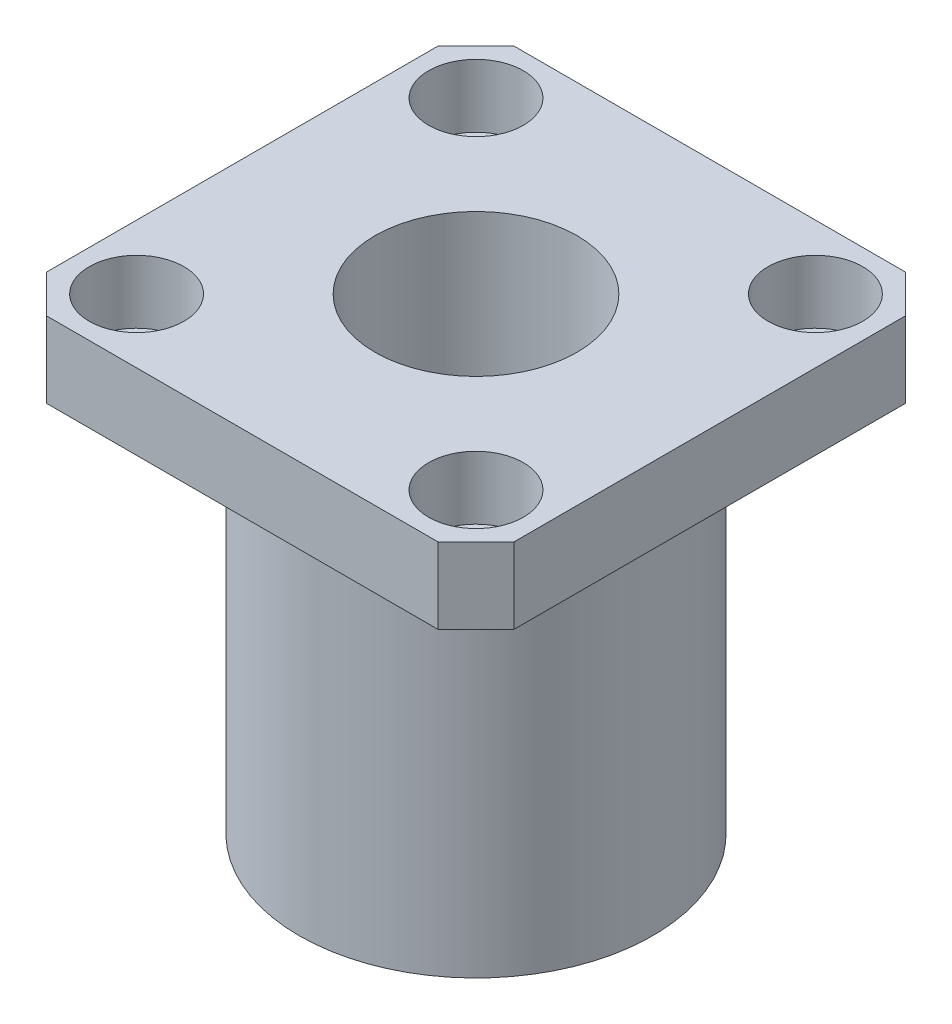
SolidWorks part; units mm, degrees
ref_plane "前视基准面" through (0, 0, 0) normal (0, 0, 1) x (1, 0, 0)
ref_plane "上视基准面" through (0, 0, 0) normal (0, 1, 0) x (1, 0, 0)
ref_plane "右视基准面" through (0, 0, 0) normal (1, 0, 0) x (0, 0, -1)
sketch "草图1" plane through (0, 0, 0) normal (0, 1, 0) x (1, 0, 0)
  circle A0 centre (0, 0) radius 8
  circle A1 centre (0, 0) radius 14
  dimension "D1" = 16
  dimension "D2" = 28
extrude "凸台-拉伸1" add sketch "草图1" along normal blind 37
sketch "草图2" plane through (0, 37, 0) normal (0, 1, 0) x (1, 0, 0)
  line L1 (18.5, -18.5) -> (-18.5, -18.5)
  line L2 (18.5, -18.5) -> (18.5, 18.5)
  line L3 (18.5, 18.5) -> (-18.5, 18.5)
  line L4 (-18.5, -18.5) -> (-18.5, 18.5)
  line L5 (18.5, -18.5) -> (-18.5, 18.5) construction
  line L6 (18.5, 18.5) -> (-18.5, -18.5) construction
  circle A0 centre (0, 0) radius 8 construction
  circle A1 centre (0, 0) radius 8
  point P0 (0, 0)
  dimension "D1" = 37
  dimension "D2" = 37
extrude "凸台-拉伸2" add sketch "草图2" against normal blind 6
hole_wizard "M3 六角头螺栓的柱形沉头孔1" positions "草图3" profile "草图4" counterbore size "M3" standard "GB" end condition up to next
sketch "草图3" plane through (0, 37, 0) normal (0, 1, 0) x (-1, 0, 0)
  line L0 (0, 0) -> (18.5, 0) construction
  line L1 (18.5, -18.5) -> (18.5, 18.5) construction
  line L3 (0, 0) -> (0, 18.5) construction
  line L4 (18.5, 18.5) -> (-18.5, 18.5) construction
  line L6 (0, 0) -> (-18.5, 18.5) construction
  circle A0 centre (0, 0) radius 19 construction
  point P0 (-13.435, 13.435)
  point P2 (13.435, 13.435)
  point P17 (13.435, -13.435)
  point P18 (-13.435, -13.435)
  dimension "D1" = 38
sketch "草图4" plane through (13.435, 37, 13.435) normal (1, 0, 0) x (0, 0, 1)
  line L0 (0, 0) -> (0, 6)
  line L1 (0, 6) -> (2.25, 6)
  line L3 (2.25, 6) -> (2.25, 5)
  line L4 (2.25, 5) -> (3.75, 5)
  line L5 (3.75, 5) -> (3.75, 0)
  line L7 (3.75, 0) -> (0, 0)
  line L11 (0, -6.35) -> (0, 107.95) construction
  dimension "通孔孔直径" = 4.5
  dimension "通孔孔深度" = 6
  dimension "柱形沉头孔直径" = 7.5
  dimension "柱形沉头孔深度" = 5
chamfer "倒角1" distance 3 angle 45 4 edges at (18.5, 34, -18.5) (-18.5, 34, -18.5) (-18.5, 34, 18.5) (18.5, 34, 18.5)
